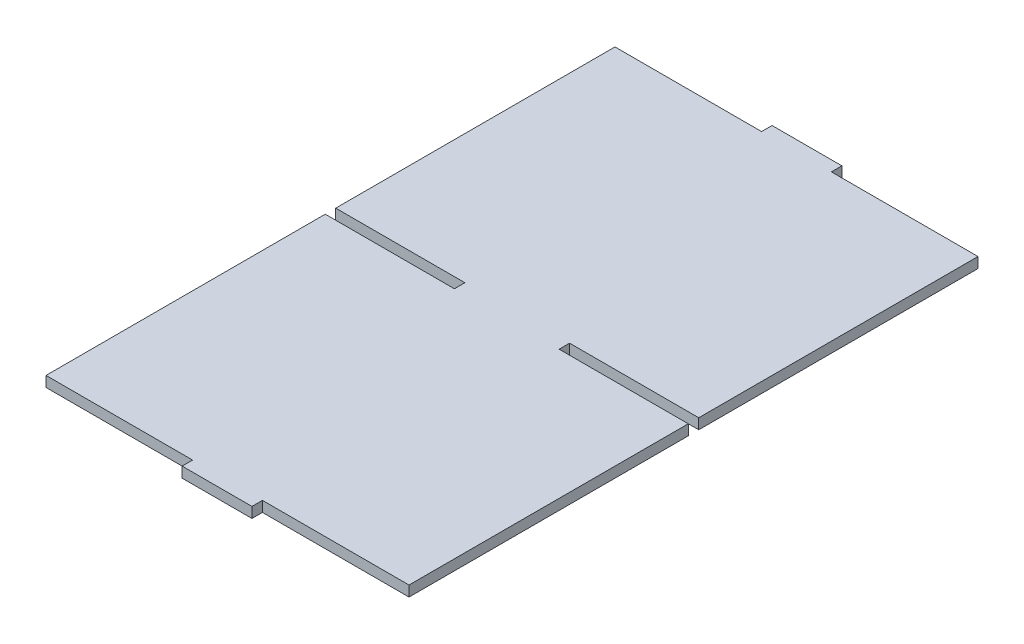
SolidWorks part; units mm, degrees
ref_plane "Front Plane" through (0, 0, 0) normal (0, 0, 1) x (1, 0, 0)
ref_plane "Top Plane" through (0, 0, 0) normal (0, 1, 0) x (1, 0, 0)
ref_plane "Right Plane" through (0, 0, 0) normal (1, 0, 0) x (0, 0, -1)
sketch "Sketch1" plane through (0, 0, 0) normal (0, 1, 0) x (1, 0, 0)
  line L0 (0, 0) -> (0, 3)
  line L1 (0, 3) -> (-42, 3)
  line L2 (-42, 3) -> (-42, 83)
  line L3 (-42, 83) -> (-5, 83)
  line L4 (-5, 83) -> (-5, 86)
  line L5 (-5, 86) -> (-42, 86)
  line L6 (-42, 86) -> (-42, 166)
  line L7 (-42, 166) -> (0, 166)
  line L8 (0, 166) -> (0, 169)
  line L9 (0, 169) -> (20, 169)
  line L10 (20, 169) -> (20, 166)
  line L11 (20, 166) -> (62, 166)
  line L12 (62, 166) -> (62, 86)
  line L13 (62, 86) -> (25, 86)
  line L14 (25, 86) -> (25, 83)
  line L15 (25, 83) -> (62, 83)
  line L16 (62, 83) -> (62, 3)
  line L17 (62, 3) -> (20, 3)
  line L18 (20, 3) -> (20, 0)
  line L19 (20, 0) -> (0, 0)
  line L20 (10, 0) -> (10, 169) construction
  point P21 (0, 0)
  point P22 (0, 0)
  point P23 (0, 0)
  point P24 (0, 0)
  point P25 (0, 0)
  dimension "D1" = 20
  dimension "D2" = 3
  dimension "D3" = 3
  dimension "D4" = 3
  dimension "D5" = 104
  dimension "D6" = 30
  dimension "D7" = 80
  dimension "D8" = 80
extrude "Boss-Extrude1" add sketch "Sketch1" along normal blind 3 contours L6 L7 L8 L9 L10 L11 L12 L13 L14 L15 L16 L17 L18 L19 L0 L1 L2 L3 L4 L5
